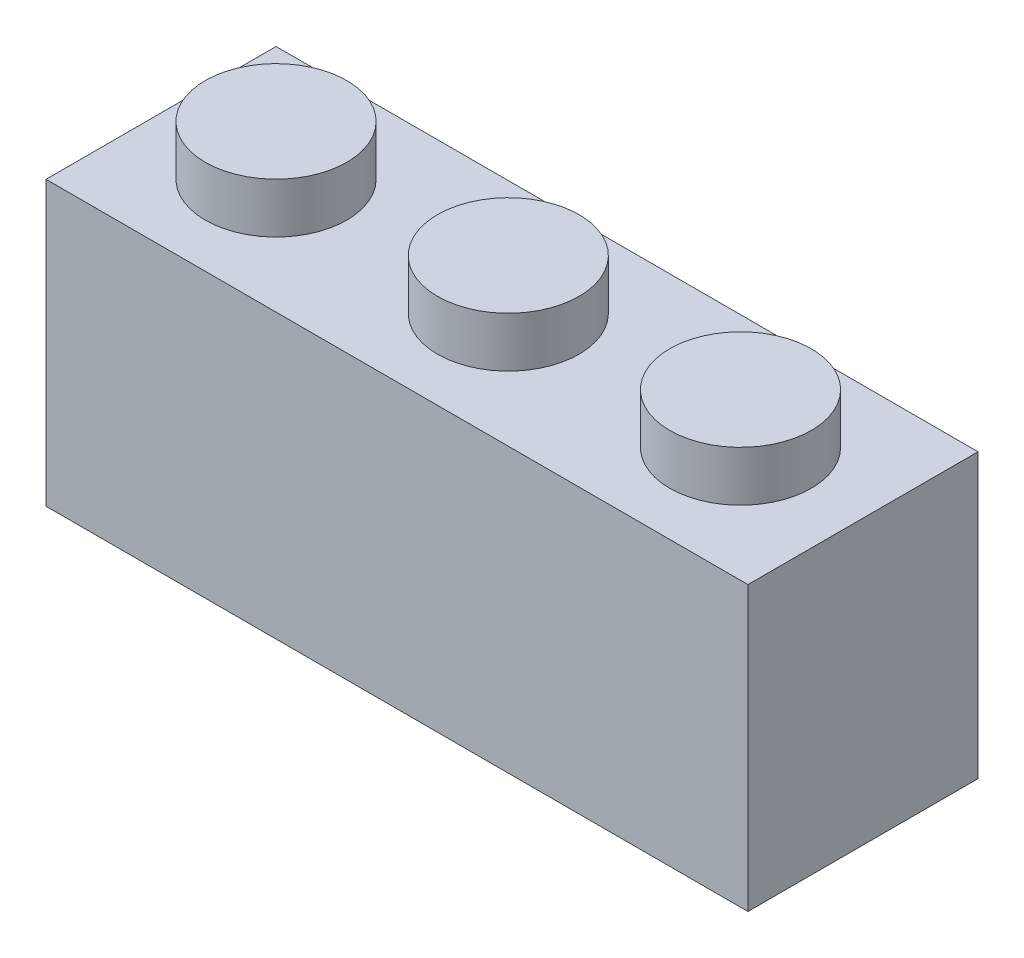
SolidWorks part; units mm, degrees
ref_plane "Спереди" through (0, 0, 0) normal (0, 0, 1) x (1, 0, 0)
ref_plane "Сверху" through (0, 0, 0) normal (0, 1, 0) x (1, 0, 0)
ref_plane "Справа" through (0, 0, 0) normal (1, 0, 0) x (0, 0, -1)
sketch "Эскиз1" plane through (0, 0, 0) normal (0, 1, 0) x (1, 0, 0)
  line L1 (11.9, -3.9) -> (-11.9, -3.9)
  line L2 (11.9, -3.9) -> (11.9, 3.9)
  line L3 (11.9, 3.9) -> (-11.9, 3.9)
  line L4 (-11.9, -3.9) -> (-11.9, 3.9)
  line L5 (11.9, -3.9) -> (-11.9, 3.9) construction
  line L6 (11.9, 3.9) -> (-11.9, -3.9) construction
  point P0 (0, 0)
  dimension "D1" = 23.8
  dimension "D2" = 7.8
extrude "Бобышка-Вытянуть2" add sketch "Эскиз1" along normal blind 9.6
sketch "Эскиз3" plane through (0, 9.6, 0) normal (0, 1, 0) x (1, 0, 0)
  line L0 (-11.9, 3.9) -> (-11.9, -3.9) construction
  line L1 (-11.9, -3.9) -> (11.9, -3.9) construction
  circle A0 centre (-8, 0) radius 2.4
  circle A1 centre (-0.126, 0) radius 2.4
  circle A2 centre (7.748, 0) radius 2.4
  dimension "D1" = 3.9
  dimension "D2" = 3.9
  dimension "D3" = 3
extrude "Бобышка-Вытянуть3" add sketch "Эскиз3" along normal blind 1.7
sketch "Эскиз4" plane through (0, 0, 0) normal (0, -1, 0) x (1, 0, 0)
  line L0 (-11.9, -3.9) -> (-11.9, 3.9) construction
  line L1 (11.9, -3.9) -> (-11.9, -3.9) construction
  circle A0 centre (-8, 0) radius 2.5
  circle A1 centre (-0.126, 0) radius 2.5
  circle A2 centre (7.748, 0) radius 2.5
  dimension "D1" = 3.9
  dimension "D2" = 3.9
  dimension "D3" = 3
extrude "Вырез-Вытянуть1" cut sketch "Эскиз4" against normal blind 1.8
